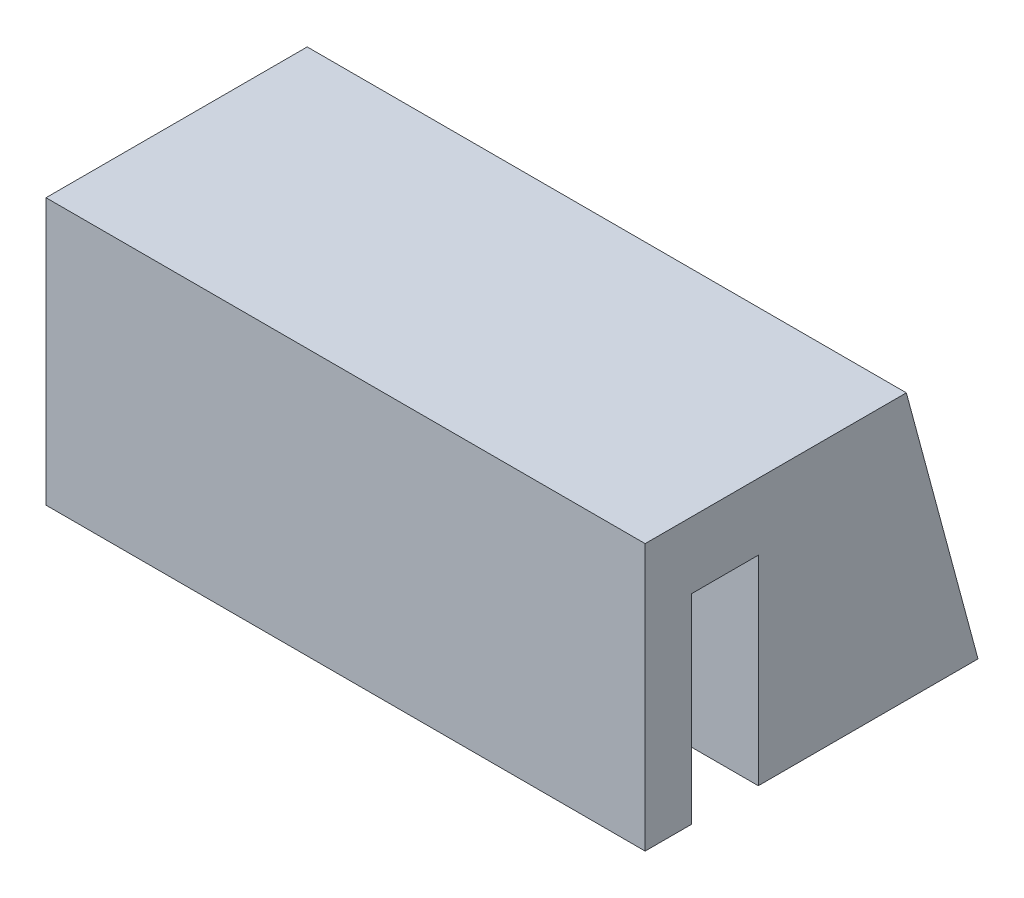
SolidWorks part; units mm, degrees
ref_plane "Front Plane" through (0, 0, 0) normal (0, 0, 1) x (1, 0, 0)
ref_plane "Top Plane" through (0, 0, 0) normal (0, 1, 0) x (1, 0, 0)
ref_plane "Right Plane" through (0, 0, 0) normal (1, 0, 0) x (0, 0, -1)
sketch "Sketch2" plane through (0, 0, 0) normal (0, 0, 1) x (1, 0, 0)
  line L1 (-22.5, -10) -> (22.5, -10)
  line L2 (-22.5, -10) -> (-22.5, 10)
  line L3 (-22.5, 10) -> (22.5, 10)
  line L4 (22.5, -10) -> (22.5, 10)
  line L5 (-22.5, -10) -> (22.5, 10) construction
  line L6 (-22.5, 10) -> (22.5, -10) construction
  point P0 (0, 0)
  dimension "D1" = 45
  dimension "D2" = 20
extrude "Boss-Extrude1" add sketch "Sketch2" along normal blind 25
sketch "Sketch5" plane through (0, 10, 0) normal (0, 1, 0) x (1, 0, 0)
  line L0 (0, 0) -> (0, -15)
  line L1 (0, -15) -> (0, -19)
  line L2 (22.5, -25) -> (22.5, 0) construction
  line L3 (-22.5, -16.5) -> (22.5, -16.5)
  line L4 (-22.5, -16.5) -> (-22.5, -21.5)
  line L5 (-22.5, -21.5) -> (22.5, -21.5)
  line L6 (22.5, -16.5) -> (22.5, -21.5)
  line L7 (-22.5, -16.5) -> (22.5, -21.5) construction
  line L8 (-22.5, -21.5) -> (22.5, -16.5) construction
  dimension "D1" = 15
  dimension "D2" = 4
  dimension "D3" = 5
extrude "Cut-Extrude1" cut sketch "Sketch5" along normal blind 15 from surface at -20
sketch "Sketch7" plane through (22.5, 0, 0) normal (1, 0, 0) x (0, 0, -1)
  line L0 (0, -10) -> (0, 10)
  line L1 (0, 10) -> (-5.3816, 10)
  line L2 (-25, 10) -> (0, 10) construction
  line L3 (-5.3816, 10) -> (0, -10)
extrude "Cut-Extrude2" cut sketch "Sketch7" against normal up to surface (45 mm away) up to face at (-22.5, -1.25, 15.75)
sketch "Sketch8" plane through (0, -0.6752, 2.5091) normal (0, 0.2598, -0.9657) x (-1, 0, 0)
  line L1 (-19.15, -4.8) -> (19.15, -4.8)
  line L2 (-19.15, -4.8) -> (-19.15, 4.8)
  line L3 (-19.15, 4.8) -> (19.15, 4.8)
  line L4 (19.15, -4.8) -> (19.15, 4.8)
  line L5 (-19.15, -4.8) -> (19.15, 4.8) construction
  line L6 (-19.15, 4.8) -> (19.15, -4.8) construction
  point P0 (0, 0)
  dimension "D1" = 38.3
  dimension "D2" = 9.6
extrude "Cut-Extrude3" cut sketch "Sketch8" against normal blind 10
sketch "Sketch9" plane through (0, -10, 0) normal (0, -1, 0) x (1, 0, 0)
  line L0 (22.5, 0) -> (-4, 0)
  line L1 (22.5, 0) -> (15.5, 0)
  line L2 (15.5, 0) -> (15.5, 16.5)
  line L3 (-22.5, 16.5) -> (22.5, 16.5) construction
  line L4 (-4, 0) -> (-4, 16.5)
  line L5 (-4, 16.5) -> (15.5, 16.5)
  line L6 (15.5, 0) -> (-4, 0)
  line M3 (22.5, 16.5) -> (-22.5, 16.5)
  line M5 (-22.5, 0) -> (22.5, 0)
  dimension "D1" = 19.5
  dimension "D2" = 7
extrude "Cut-Extrude4" cut sketch "Sketch9" against normal up to surface (10.5309 mm away) contours L4 L2 M5 M3
